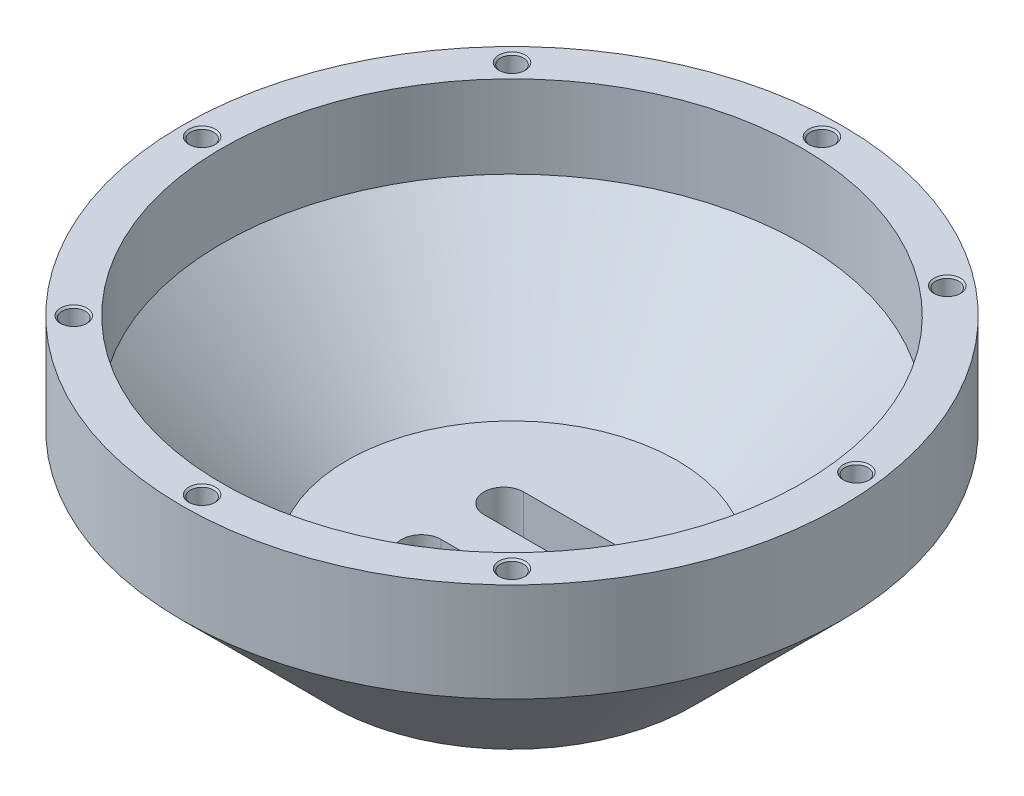
SolidWorks part; units mm, degrees
material "ABS"
ref_plane "Front Plane" through (0, 0, 0) normal (0, 0, 1) x (1, 0, 0)
ref_plane "Top Plane" through (0, 0, 0) normal (0, 1, 0) x (1, 0, 0)
ref_plane "Right Plane" through (0, 0, 0) normal (1, 0, 0) x (0, 0, -1)
sketch "Sketch2" plane through (0, 0, 0) normal (0, 0, 1) x (1, 0, 0)
  line L0 (55, 0) -> (100, 45)
  line L1 (0, 0) -> (55, 0)
  line L2 (0, 0) -> (0, 12)
  line L3 (0, 12) -> (50.0294, 12)
  line L10 (88, 75) -> (100, 75)
  line L11 (88, 75) -> (88, 49.9706)
  line L13 (100, 75) -> (100, 45)
  line L15 (50.0294, 12) -> (88, 49.9706)
  point P6 (94, 75)
  dimension "D1" = 12
  dimension "D2" = 55
  dimension "D3" = 12
  dimension "D4" = 100
  dimension "D5" = 45
  dimension "D6" = 12
  dimension "D7" = 75
revolve "Revolve1" add sketch "Sketch2" angle 360 about L2
sketch "Sketch3" plane through (0, 0, 0) normal (0, -1, 0) x (1, 0, 0)
  line L0 (-100, 0) -> (100, 0) construction
  line L1 (-15, 18.5) -> (15, 18.5)
  line L3 (-15, 6.5) -> (15, 6.5)
  line L5 (0, 100) -> (0, -100) construction
  line L6 (-15, -6.5) -> (15, -6.5)
  line L8 (-15, -18.5) -> (15, -18.5)
  circle A0 centre (0, 0) radius 100 construction
  arc A1 (15, 18.5) -> (15, 6.5) centre (15, 12.5) cw
  arc A2 (-15, 6.5) -> (-15, 18.5) centre (-15, 12.5) cw
  arc A3 (15, -6.5) -> (15, -18.5) centre (15, -12.5) cw
  arc A4 (-15, -18.5) -> (-15, -6.5) centre (-15, -12.5) cw
  point P15 (0, 0)
  point P17 (0, 0)
  point P19 (-21, 12.5)
  dimension "D1" = 12
  dimension "D2" = 30
  dimension "D3" = 12.5
  dimension "D4" = 15
extrude "Cut-Extrude1" cut sketch "Sketch3" against normal through all
hole_wizard "M8x1.0 Tapped Hole2" positions "Sketch20" profile "Sketch21" tap size "M8x1.0" standard "ANSI Metric"
sketch "Sketch20" plane through (0, 75, 0) normal (0, 1, 0) x (1, 0, 0)
  line L0 (0, 94) -> (0, 0) construction
  line L1 (0, 0) -> (58.1394, 73.8635) construction
  line L2 (58.1394, 73.8635) -> (0, 0) construction
  line L3 (0, 0) -> (93.3401, 11.1186) construction
  line L5 (66.468, -66.468) -> (0, 0) construction
  line L6 (0, 0) -> (0, -94) construction
  line L7 (0, -94) -> (-66.468, -66.468) construction
  line L8 (-66.468, -66.468) -> (0, 0) construction
  line L9 (0, 0) -> (-94, 0) construction
  line L10 (-94, 0) -> (-66.468, 66.468) construction
  line L11 (-66.468, 66.468) -> (0, 0) construction
  circle A0 centre (0, 0) radius 94
  point P0 (0, 94)
  point P2 (58.1394, 73.8635)
  point P4 (93.3401, 11.1186)
  point P6 (66.468, -66.468)
  point P8 (0, -94)
  point P10 (-66.468, -66.468)
  point P12 (-94, 0)
  point P14 (-66.468, 66.468)
  point P39 (0, 0)
  dimension "D1" = 188
  dimension "D2" = 38.207
  dimension "D3" = 45
  dimension "D4" = 45
  dimension "D5" = 45
  dimension "D6" = 45
  dimension "D7" = 45
  dimension "D8" = 45
sketch "Sketch21" plane through (0, 75, -94) normal (1, 0, 0) x (0, 0, 1)
  line L0 (0, 0) -> (0, 23.103)
  line L1 (0, 23.103) -> (3.5, 21)
  line L2 (3.5, 21) -> (3.5, 0.525)
  line L3 (3.5, 0.525) -> (4.025, 0)
  line L5 (4.025, 0) -> (0, 0)
  line L6 (-3.5, 0.525) -> (-4.025, 0) construction
  line L10 (0, 23.103) -> (-3.5, 21) construction
  line L11 (0, -6.35) -> (0, 107.95) construction
  dimension "Tap Drill Dia." = 7
  dimension "Tap Drill Depth" = 21
  dimension "Near C'Sink Dia." = 8.05
  dimension "Near C'Sink Angle" = 90
  dimension "Drill Angle" = 118
cosmetic thread "Hole Thread8" parameters "D1"=16, "D2"=8
cosmetic thread "Hole Thread9" parameters "D1"=16, "D2"=8
cosmetic thread "Hole Thread10" parameters "D1"=16, "D2"=8
cosmetic thread "Hole Thread11" parameters "D1"=16, "D2"=8
cosmetic thread "Hole Thread12" parameters "D1"=16, "D2"=8
cosmetic thread "Hole Thread13" parameters "D1"=16, "D2"=8
cosmetic thread "Hole Thread14" parameters "D1"=16, "D2"=8
cosmetic thread "Hole Thread15" parameters "D1"=16, "D2"=8
